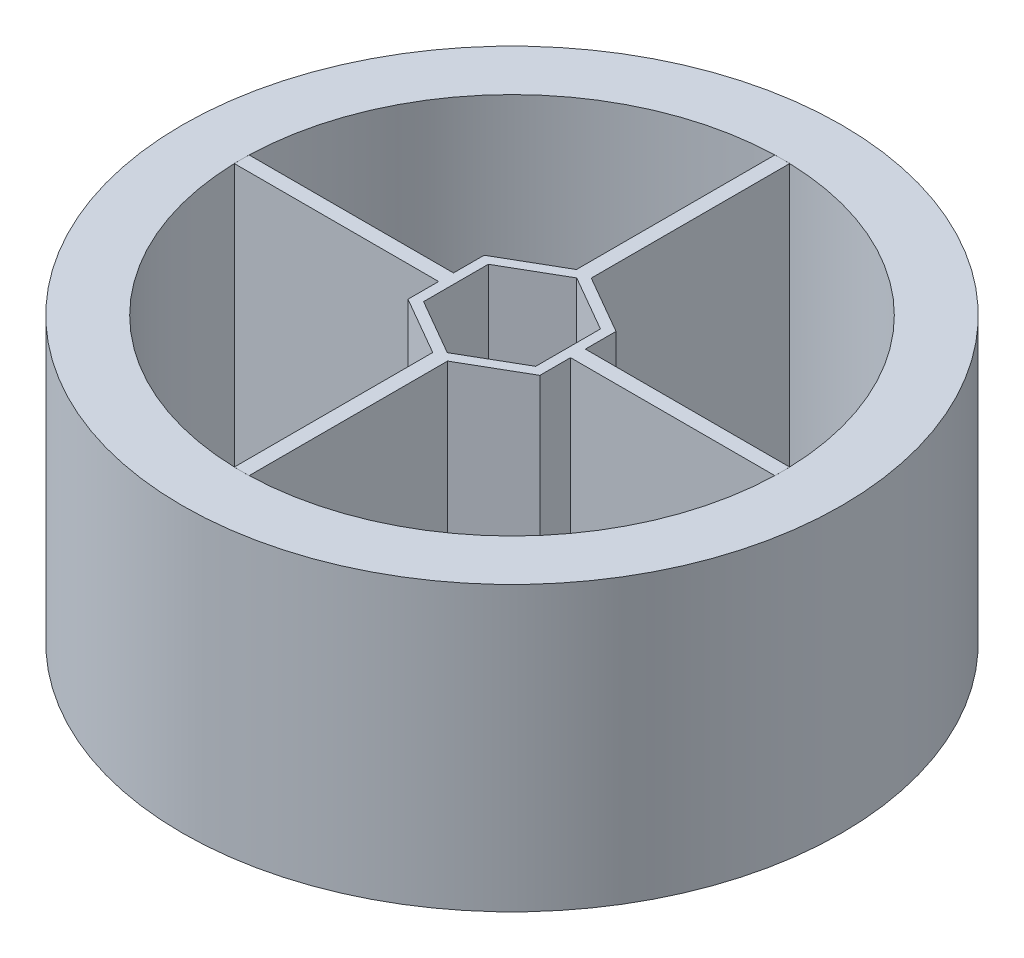
SolidWorks part; units mm, degrees
ref_plane "Front Plane" through (0, 0, 0) normal (0, 0, 1) x (1, 0, 0)
ref_plane "Top Plane" through (0, 0, 0) normal (0, 1, 0) x (1, 0, 0)
ref_plane "Right Plane" through (0, 0, 0) normal (1, 0, 0) x (0, 0, -1)
sketch "Sketch1" plane through (0, 0, 0) normal (0, 1, 0) x (1, 0, 0)
  line L0 (-1.125, -41) -> (-1.125, 41)
  line L1 (-1.125, -41) -> (1.125, -41)
  line L2 (-1.125, 41) -> (1.125, 41)
  line L3 (1.125, -41) -> (1.125, 41)
  line L4 (-1.125, -41) -> (1.125, 41) construction
  line L5 (-1.125, 41) -> (1.125, -41) construction
  line L6 (-41, 1.125) -> (41, 1.125)
  line L7 (-41, 1.125) -> (-41, -1.125)
  line L8 (41, 1.125) -> (41, -1.125)
  line L9 (-41, -1.125) -> (41, -1.125)
  line L10 (-41, 1.125) -> (41, -1.125) construction
  line L11 (41, 1.125) -> (-41, -1.125) construction
  line L13 (0, 11.547) -> (-10, 5.7735)
  line L14 (-10, 5.7735) -> (-10, -5.7735)
  line L15 (-10, -5.7735) -> (0, -11.547)
  line L16 (0, -11.547) -> (10, -5.7735)
  line L17 (10, -5.7735) -> (10, 5.7735)
  line L18 (10, 5.7735) -> (0, 11.547)
  circle A0 centre (0, 0) radius 50
  circle A1 centre (0, 0) radius 41
  circle A2 centre (0, 0) radius 10 construction
  dimension "D1" = 100
  dimension "D2" = 82
  dimension "D3" = 2.25
  dimension "D4" = 2.25
  dimension "D5" = 20
  dimension "D6" = 82
  dimension "D7" = 82
extrude "main-wheel" add sketch "Sketch1" along normal blind 43 contours A0 A1 L3 L1 L0 L9 L7 L6 L2 L8 | L6 A1 L9 L14 | L9 A1 L6 L17 | L3 A1 L0 L13 L18 | A1 L3 L16 L15 L0 | L14 L15 L0 L9 | L6 L14 L9 L0 | L9 L17 L6 L3 | L16 L17 L9 L3 | L15 L16 L3 L9 L0 | L0 L9 L3 L6 | L3 L18 L13 L0 L6 | L17 L18 L3 L6 | L13 L14 L6 L0
sketch "Sketch2" plane through (0, 43, 0) normal (0, 1, 0) x (1, 0, 0)
  line L1 (0, -9.815) -> (8.5, -4.9075)
  line L2 (8.5, -4.9075) -> (8.5, 4.9075)
  line L3 (8.5, 4.9075) -> (0, 9.815)
  line L4 (0, 9.815) -> (-8.5, 4.9075)
  line L5 (-8.5, 4.9075) -> (-8.5, -4.9075)
  line L6 (-8.5, -4.9075) -> (0, -9.815)
  circle A0 centre (0, 0) radius 8.5 construction
  dimension "D1" = 17
extrude "hex-bore" cut sketch "Sketch2" against normal blind 23
sketch "Sketch3" plane through (0, 20, 0) normal (0, 1, 0) x (1, 0, 0)
  circle A0 centre (0, 0) radius 2.5
  dimension "D1" = 5
extrude "motor-bore" cut sketch "Sketch3" against normal through all
